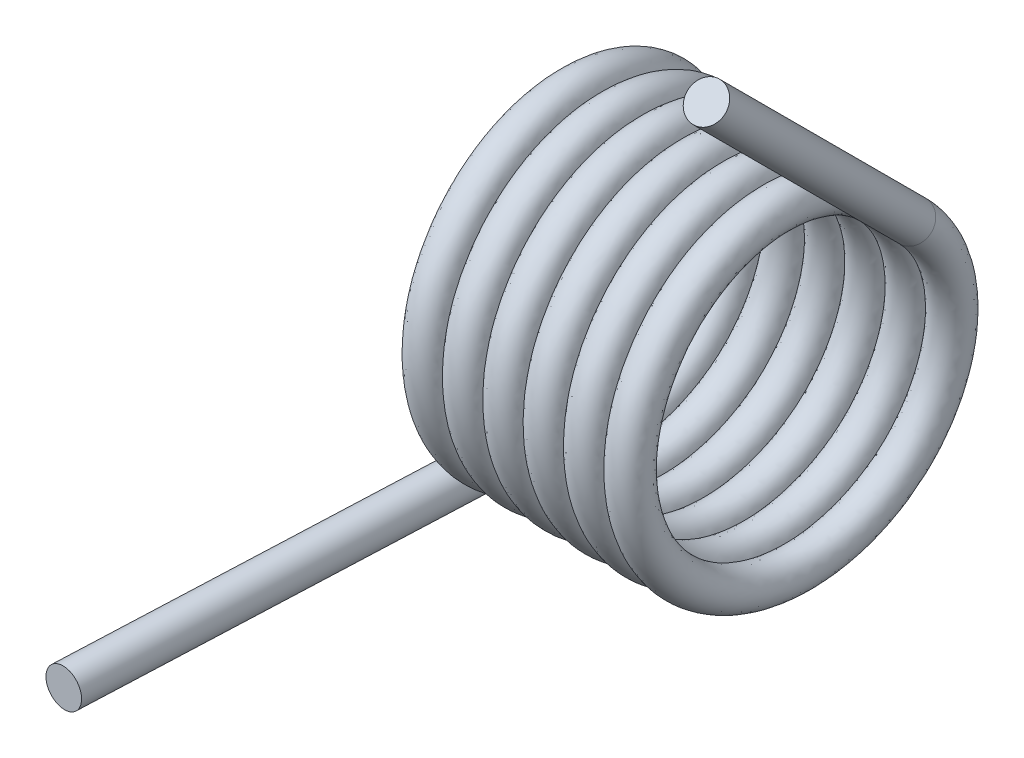
SolidWorks part; units mm, degrees
ref_plane "Front" through (0, 0, 0) normal (0, 0, 1) x (1, 0, 0)
ref_plane "Top" through (0, 0, 0) normal (0, 1, 0) x (1, 0, 0)
ref_plane "Right" through (0, 0, 0) normal (1, 0, 0) x (0, 0, -1)
sketch "Sketch1" plane through (0, 0, 0) normal (1, 0, 0) x (0, 0, -1)
  line L0 (0, 0) -> (0, -1.0795) construction
  line L1 (0, -1.0795) -> (0, -1.2319) construction
  line L2 (0, -1.2319) -> (0, -1.3843) construction
  circle A0 centre (0, 0) radius 1.0795 construction
  circle A1 centre (0, 0) radius 1.3843 construction
  circle A2 centre (0, 0) radius 1.2319
  circle A3 centre (0, -1.2319) radius 0.1524 construction
  circle A4 centre (0, 0) radius 0.8509 construction
curve "Helix/Spiral1" pitch 0.3302 height 2.105 turns 6.375
ref_plane "Plane1" through (0, -1.2319, 0) normal (0.0426, 0, -0.9991) x (-0.9991, 0, -0.0426)
sketch "Sketch2" plane through (0, -1.2319, 0) normal (0.0426, 0, -0.9991) x (-0.9991, 0, -0.0426)
  circle A0 centre (0, 0) radius 0.1524
  dimension "D1" = 0.3048
sweep "Sweep1" add profiles "Sketch2" path "Helix/Spiral1"
sketch "Sketch3" plane through (0, 0, 0) normal (-0.0426, 0, 0.9991) x (0.9991, 0, 0.0426)
  circle A1 centre (0, -1.2319) radius 0.1524
  circle A2 centre (0, -1.2319) radius 0.1524
  dimension "D1" = 0
extrude "Extrude1" add sketch "Sketch3" along normal blind 3.81
sketch "Sketch4" plane through (0.0038, 0.0634, 0.0634) normal (0.0426, 0.7065, 0.7065) x (-0.9779, 0.1743, -0.1153)
  circle A1 centre (-1.8063, -1.6364) radius 0.1524
  circle A2 centre (-1.8063, -1.6364) radius 0.1524
  dimension "D1" = 0
extrude "Extrude2" add sketch "Sketch4" along normal blind 2.54
sketch "Sketch5" plane through (0, 0, 0) normal (1, 0, 0) x (0, 0, -1)
  circle A0 centre (0, 0) radius 0.8509 construction
  circle A1 centre (0, 0) radius 0.8509
equation "\"D4@Helix/Spiral1\"=\"Wire Dia@Sketch1\"+.001"
equation "\"D1@Sketch2\"=\"Wire Dia@Sketch1\""
